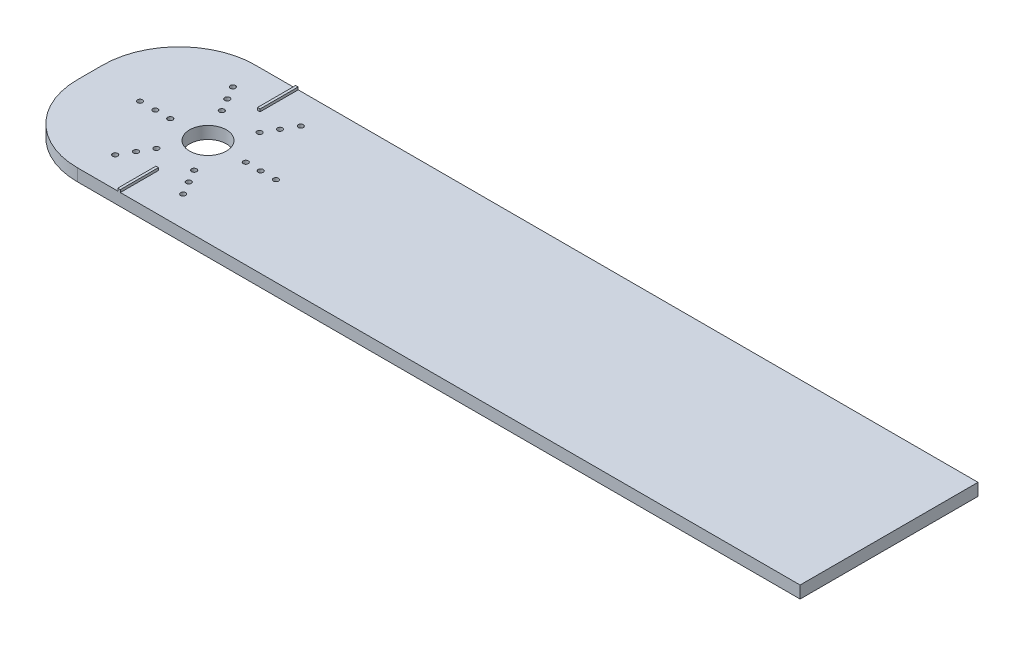
SolidWorks part; units mm, degrees
ref_plane "Front Plane" through (0, 0, 0) normal (0, 0, 1) x (1, 0, 0)
ref_plane "Top Plane" through (0, 0, 0) normal (0, 1, 0) x (1, 0, 0)
ref_plane "Right Plane" through (0, 0, 0) normal (1, 0, 0) x (0, 0, -1)
sketch "Sketch1" plane through (0, 0, 0) normal (0, 1, 0) x (1, 0, 0)
  line L1 (-29.6771, 38.9958) -> (127.5229, 38.9958)
  line L2 (-29.6771, 38.9958) -> (-29.6771, 3.9958)
  line L3 (-29.6771, 3.9958) -> (127.5229, 3.9958)
  line L4 (127.5229, 38.9958) -> (127.5229, 3.9958)
  dimension "D1" = 157.2
  dimension "D2" = 35
extrude "Boss-Extrude1" add sketch "Sketch1" along normal blind 2.4
sketch "Sketch2" plane through (0, 2.4, 0) normal (0, 1, 0) x (1, 0, 0)
  line L0 (-6.4771, 38.9958) -> (-6.4771, 2.4158) construction
  line L1 (127.5229, 38.9958) -> (-29.6771, 38.9958) construction
  line L2 (-29.6771, 21.4958) -> (127.5229, 21.4958) construction
  line L3 (-29.6771, 38.9958) -> (-29.6771, 3.9958) construction
  line L4 (127.5229, 3.9958) -> (127.5229, 38.9958) construction
  circle A4 centre (-6.4771, 21.4958) radius 3.625
  circle A5 centre (-13.9071, 21.4958) radius 0.5
  circle A6 centre (-16.8421, 21.4958) radius 0.5
  circle A7 centre (-19.8471, 21.4958) radius 0.5
  circle A19 centre (-10.1921, 27.9303) radius 0.5
  circle A20 centre (-11.6596, 30.4721) radius 0.5
  circle A21 centre (-13.1621, 33.0745) radius 0.5
  circle A22 centre (-2.7621, 27.9303) radius 0.5
  circle A23 centre (-1.2946, 30.4721) radius 0.5
  circle A24 centre (0.2079, 33.0745) radius 0.5
  circle A25 centre (0.9529, 21.4958) radius 0.5
  circle A26 centre (3.8879, 21.4958) radius 0.5
  circle A27 centre (6.8929, 21.4958) radius 0.5
  circle A28 centre (-2.7621, 15.0612) radius 0.5
  circle A29 centre (-1.2946, 12.5194) radius 0.5
  circle A30 centre (0.2079, 9.917) radius 0.5
  circle A31 centre (-10.1921, 15.0612) radius 0.5
  circle A32 centre (-11.6596, 12.5194) radius 0.5
  circle A33 centre (-13.1621, 9.917) radius 0.5
  point P11 (-6.4771, 21.4958)
  point P24 (-6.4771, 21.4958)
  point P84 (-6.4771, 21.4958)
  dimension "D11" = 7.25
  dimension "D12" = 7.43
  dimension "D13" = 10.365
  dimension "D14" = 13.37
  dimension "D15" = 1
  dimension "D16" = 1
  dimension "D17" = 1
  dimension "D1" = 23.2
  dimension "D2" = 6
extrude "Cut-Extrude1" cut sketch "Sketch2" against normal blind 2.4
sketch "Sketch6" plane through (0, 2.4, 0) normal (0, 1, 0) x (1, 0, 0)
  line L0 (-29.6771, 21.4958) -> (127.5229, 21.4958) construction
  line L1 (-29.6771, 38.9958) -> (-29.6771, 3.9958) construction
  line L2 (127.5229, 3.9958) -> (127.5229, 38.9958) construction
  line L3 (-6.4771, 21.4958) -> (-6.4771, 38.9958) construction
  line L4 (127.5229, 38.9958) -> (-29.6771, 38.9958) construction
  line L5 (-6.2271, 3.9958) -> (-6.2271, 11.4958)
  line L6 (-6.7271, 38.9958) -> (-6.2271, 38.9958)
  line L7 (-6.7271, 38.9958) -> (-6.7271, 31.4958)
  line L8 (-6.7271, 31.4958) -> (-6.2271, 31.4958)
  line L9 (-6.2271, 38.9958) -> (-6.2271, 31.4958)
  line L10 (-6.7271, 11.4958) -> (-6.2271, 11.4958)
  line L11 (-6.7271, 3.9958) -> (-6.7271, 11.4958)
  line L12 (-6.7271, 3.9958) -> (-6.2271, 3.9958)
  dimension "D1" = 0.25
  dimension "D2" = 0.5
  dimension "D3" = 7.5
extrude "Boss-Extrude3" add sketch "Sketch6" along normal blind 0.5
fillet "Fillet3" radius 15 2 edges at (-29.6771, 1.2, -3.9958) (-29.6771, 1.2, -38.9958)
